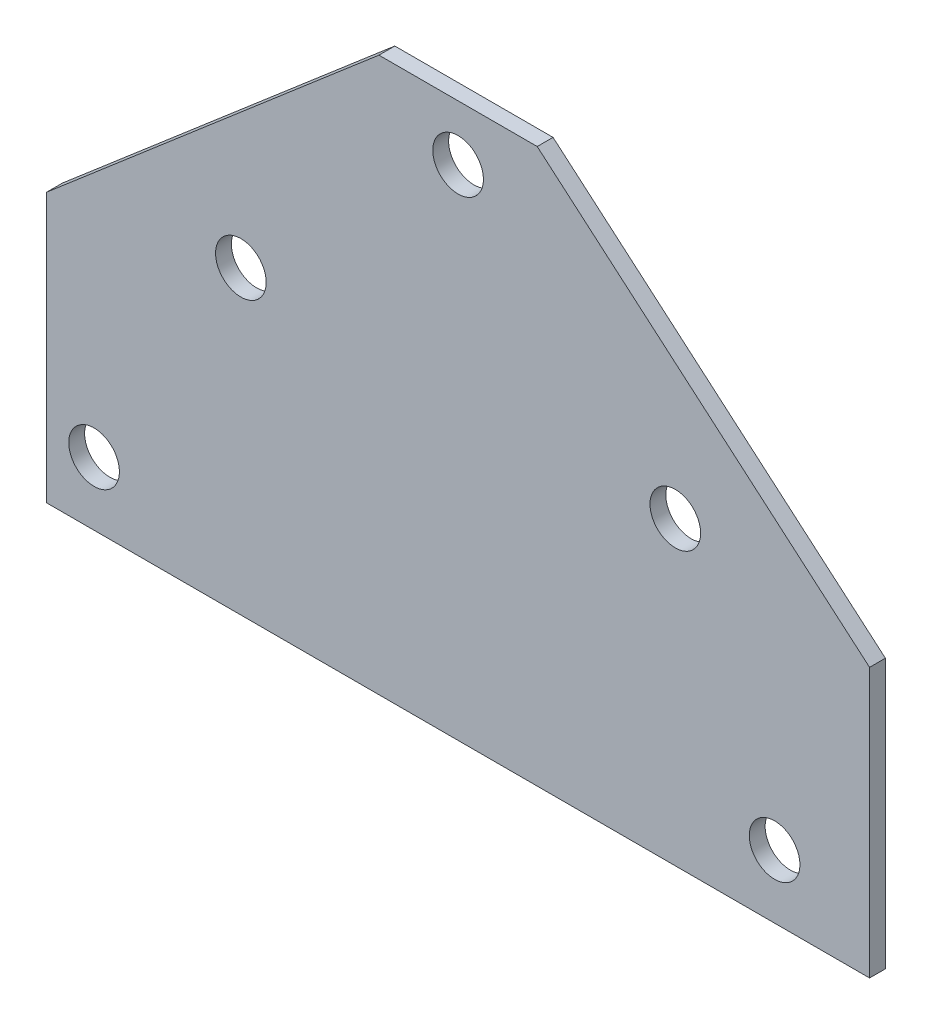
SolidWorks part; units mm, degrees
ref_plane "前视基准面" through (0, 0, 0) normal (0, 0, 1) x (1, 0, 0)
ref_plane "上视基准面" through (0, 0, 0) normal (0, 1, 0) x (1, 0, 0)
ref_plane "右视基准面" through (0, 0, 0) normal (1, 0, 0) x (0, 0, -1)
sketch "草图1" plane through (0, 0, 0) normal (0, 0, 1) x (1, 0, 0)
  line L5 (26, 0) -> (-26, 0)
  line L6 (-26, 0) -> (-26, 17)
  line L7 (-26, 17) -> (-5, 35)
  line L8 (-5, 35) -> (5, 35)
  line L9 (0, 10.6302) -> (0, -10.7017) construction
  line L10 (26, 17) -> (5, 35)
  line L11 (26, 0) -> (26, 17)
  circle A0 centre (-13.725, 19) radius 1.6
  circle A1 centre (13.725, 19) radius 1.6
  circle A2 centre (-23, 4) radius 1.6
  circle A3 centre (20, 4) radius 1.6
  circle A4 centre (0, 31.5) radius 1.6
  point P10 (0, 35)
  point P12 (0, 0)
  dimension "D5" = 3.2
  dimension "D6" = 27.45
  dimension "D7" = 4
  dimension "D8" = 3.2
  dimension "D9" = 15
  dimension "D10" = 23
  dimension "D11" = 3.2
  dimension "D12" = 3.2
  dimension "D14" = 12.5
  dimension "D1" = 52
  dimension "D2" = 35
  dimension "D3" = 17
  dimension "D4" = 10
  dimension "D13" = 20
extrude "凸台-拉伸1" add sketch "草图1" along normal blind 1
